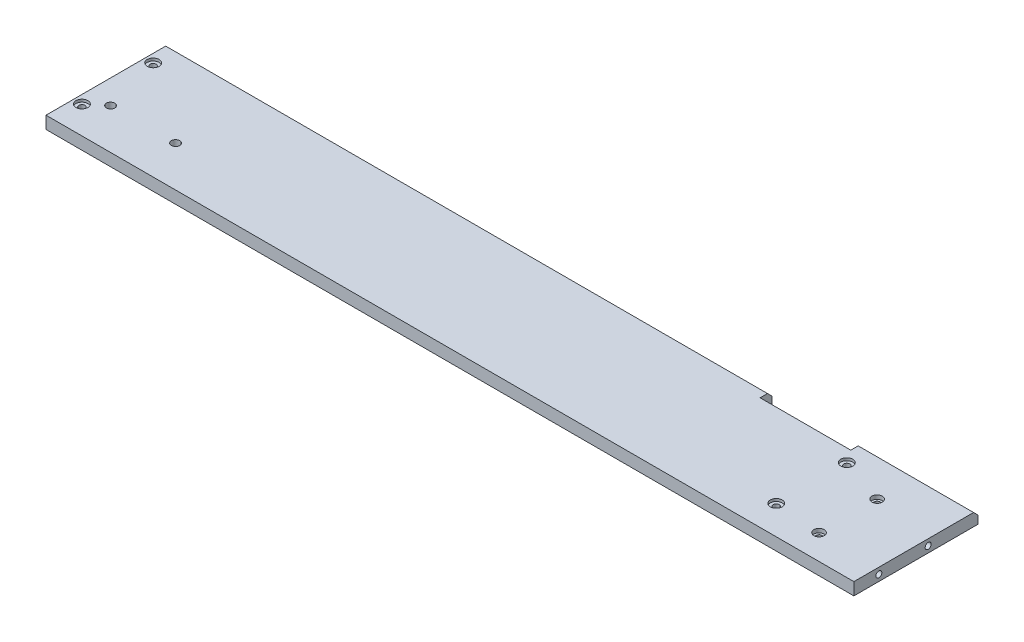
SolidWorks part; units mm, degrees
material "1060 Alloy"
ref_plane "Front Plane" through (0, 0, 0) normal (0, 0, 1) x (1, 0, 0)
ref_plane "Top Plane" through (0, 0, 0) normal (0, 1, 0) x (1, 0, 0)
ref_plane "Right Plane" through (0, 0, 0) normal (1, 0, 0) x (0, 0, -1)
sketch "Sketch1" plane through (0, 0, 0) normal (0, 1, 0) x (1, 0, 0)
  line L1 (0, 0) -> (622, 0)
  line L2 (0, 0) -> (0, -95.56)
  line L3 (0, -95.56) -> (622, -95.56)
  line L4 (622, 0) -> (622, -95.56)
  dimension "D1" = 622
  dimension "D2" = 95.56
extrude "Boss-Extrude1" add sketch "Sketch1" along normal blind 9.55
hole_wizard "Hole2" positions "Sketch5" profile "Sketch4" legacy end condition through all
sketch "Sketch5" plane through (0, 9.55, 0) normal (0, 1, 0) x (-1, 0, 0)
  line L0 (0, 0) -> (0, 95.56) construction
  line L1 (0, 95.56) -> (-622, 95.56) construction
  point P0 (-18.475, 64.285)
  point P1 (-68.475, 64.285)
  dimension "D1" = 18.475
  dimension "D2" = 31.275
  dimension "D3" = 31.275
  dimension "D4" = 68.475
sketch "Sketch4" plane through (18.475, 9.55, 64.285) normal (1, 0, 0) x (0, 0, 1)
  line L0 (0, 0) -> (0, 9.55)
  line L1 (0, 9.55) -> (3.25, 9.55)
  line L2 (3.25, 9.55) -> (3.25, 0)
  line L3 (3.25, 0) -> (0, 0)
  line L4 (0, 110) -> (0, -10) construction
  dimension "Diameter" = 6.5
  dimension "Depth" = 9.55
hole_wizard "Hole5" positions "Sketch13" profile "Sketch12" legacy end condition through all
sketch "Sketch13" plane through (0, 9.55, 0) normal (0, 1, 0) x (-1, 0, 0)
  line L0 (0, 95.56) -> (-622, 95.56) construction
  line L1 (0, 0) -> (0, 95.56) construction
  line L2 (-622, 0) -> (0, 0) construction
  line L3 (-622, 95.56) -> (-622, 0) construction
  point P0 (-6.4, 19.45)
  point P1 (-6.4, 74.31)
  point P3 (-539.95, 18.95)
  point P5 (-539.95, 73.28)
  dimension "D1" = 21.25
  dimension "D2" = 54.86
  dimension "D3" = 6.4
  dimension "D4" = 6.4
  dimension "D5" = 18.95
  dimension "D6" = 54.33
  dimension "D7" = 82.05
  dimension "D8" = 82.05
sketch "Sketch12" plane through (6.4, 9.55, 19.45) normal (1, 0, 0) x (0, 0, 1)
  line L0 (0, 0) -> (0, 9.55)
  line L1 (0, 9.55) -> (2.3, 9.55)
  line L2 (2.3, 9.55) -> (2.3, 2)
  line L3 (2.3, 2) -> (4.6, 2)
  line L4 (4.6, 2) -> (4.6, 0)
  line L5 (4.6, 0) -> (0, 0)
  line L6 (0, 110) -> (0, -10) construction
  dimension "Diameter" = 4.6
  dimension "Depth" = 9.55
  dimension "C-Bore Diameter" = 9.2
  dimension "C-Bore Depth" = 2
hole_wizard "Hole6" positions "Sketch15" profile "Sketch14" legacy end condition through all
sketch "Sketch15" plane through (0, 9.55, 0) normal (0, 1, 0) x (-1, 0, 0)
  line L0 (-622, 95.56) -> (-622, 0) construction
  line L2 (-622, 0) -> (0, 0) construction
  point P0 (-575.95, 31.61)
  point P1 (-575.95, 76.32)
  dimension "D1" = 46.05
  dimension "D2" = 46.05
  dimension "D3" = 31.61
  dimension "D4" = 44.71
sketch "Sketch14" plane through (575.95, 9.55, 31.61) normal (1, 0, 0) x (0, 0, 1)
  line L0 (0, 0) -> (0, 9.55)
  line L1 (0, 9.55) -> (2.3, 9.55)
  line L2 (2.3, 9.55) -> (2.3, 3)
  line L3 (2.3, 3) -> (4, 3)
  line L4 (4, 3) -> (4, 0)
  line L5 (4, 0) -> (0, 0)
  line L6 (0, 110) -> (0, -10) construction
  dimension "Diameter" = 4.6
  dimension "Depth" = 9.55
  dimension "C-Bore Diameter" = 8
  dimension "C-Bore Depth" = 3
chamfer "Chamfer1" distance 3.4 angle 45 1 edges at (311, 9.55, 0)
sketch "Sketch16" plane through (0, 0, 0) normal (0, -1, 0) x (1, 0, 0)
  line L0 (622, 0) -> (0, 0) construction
  line L1 (533.15, 0) -> (463.34, 0)
  line L2 (533.15, 0) -> (533.15, 9.1)
  line L3 (533.15, 9.1) -> (463.34, 9.1)
  line L4 (463.34, 0) -> (463.34, 9.1)
  line L5 (622, 95.56) -> (622, 0) construction
  dimension "D1" = 88.85
  dimension "D2" = 9.1
  dimension "D3" = 69.81
extrude "Cut-Extrude1" cut sketch "Sketch16" against normal through all
hole_wizard "Hole7" positions "Sketch18" profile "Sketch17" legacy
sketch "Sketch18" plane through (622, 0, 0) normal (1, 0, 0) x (0, 0, -1)
  line L0 (-95.56, 9.55) -> (-95.56, 0) construction
  line L1 (-95.56, 9.55) -> (-3.4, 9.55) construction
  line L2 (-95.56, 0) -> (0, 0) construction
  point P0 (-76.36, 4.775)
  point P1 (-38.38, 4.775)
  point P4 (-95.56, 4.775)
  dimension "D1" = 19.2
  dimension "D2" = 37.98
  dimension "D3" = 4.775
  dimension "D4" = 4.775
sketch "Sketch17" plane through (622, 4.775, 76.36) normal (0, 1, 0) x (0, 0, -1)
  line L0 (0, 0) -> (0, 20)
  line L1 (0, 20) -> (2.3, 20)
  line L2 (2.3, 20) -> (2.3, 0)
  line L3 (2.3, 0) -> (0, 0)
  line L4 (0, 110) -> (0, -10) construction
  dimension "Diameter" = 4.6
  dimension "Depth" = 20
equation "\"D3@Sketch5\"=\"D2@Sketch5\""
equation "\"D3@Sketch13\" = \"D4@Sketch13\""
equation "\"D8@Sketch13\"=\"D7@Sketch13\""
equation "\"D1@Sketch15\" = \"D2@Sketch15\""
equation "\"D3@Sketch18\"=(\"D1@Boss-Extrude1\" /2)"
equation "\"D4@Sketch18\" = \"D3@Sketch18\""
